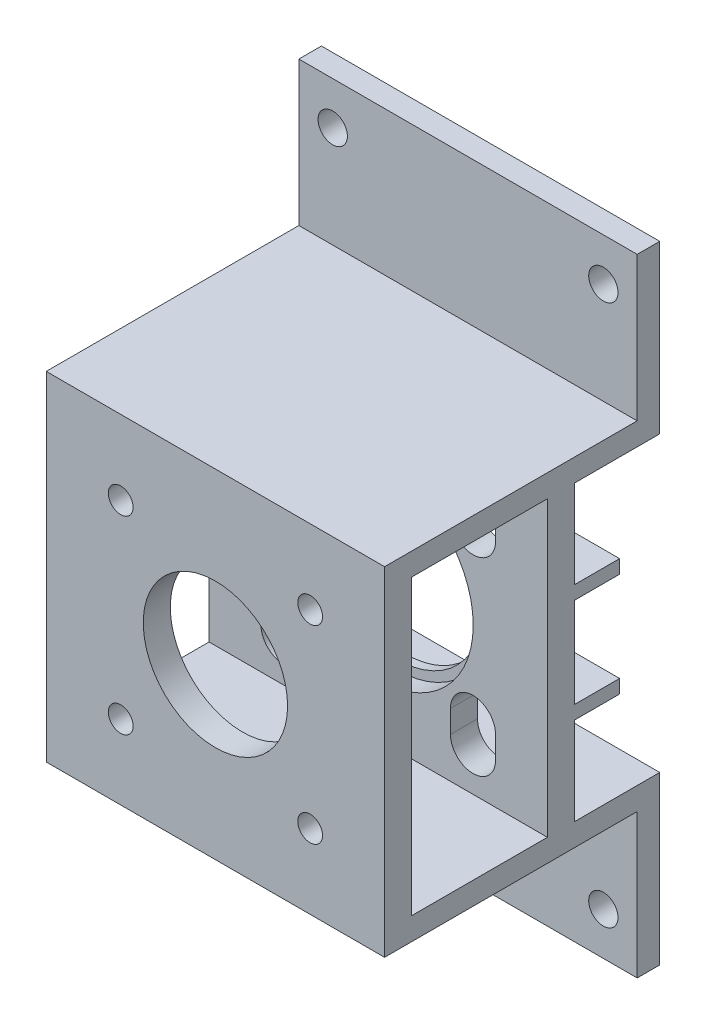
SolidWorks part; units mm, degrees
ref_plane "Front Plane" through (0, 0, 0) normal (0, 0, 1) x (1, 0, 0)
ref_plane "Top Plane" through (0, 0, 0) normal (0, 1, 0) x (1, 0, 0)
ref_plane "Right Plane" through (0, 0, 0) normal (1, 0, 0) x (0, 0, -1)
sketch "Sketch1" plane through (0, 0, 0) normal (0, 0, 1) x (1, 0, 0)
  line L1 (-37.5, -37.5) -> (37.5, -37.5)
  line L2 (-37.5, -37.5) -> (-37.5, 37.5)
  line L3 (-37.5, 37.5) -> (37.5, 37.5)
  line L4 (37.5, -37.5) -> (37.5, 37.5)
  line L5 (-37.5, -37.5) -> (37.5, 37.5) construction
  line L6 (-37.5, 37.5) -> (37.5, -37.5) construction
  line L7 (-21, -21) -> (21, -21) construction
  line L8 (-21, -21) -> (-21, 21) construction
  line L9 (-21, 21) -> (21, 21) construction
  line L10 (21, -21) -> (21, 21) construction
  line L11 (-21, -21) -> (21, 21) construction
  line L12 (-21, 21) -> (21, -21) construction
  circle A0 centre (21, 21) radius 2.75
  circle A1 centre (21, -21) radius 2.75
  circle A2 centre (-21, -21) radius 2.75
  circle A3 centre (-21, 21) radius 2.75
  circle A5 centre (0, 0) radius 16
  point P0 (0, 0)
  point P6 (0, 0)
  point P21 (0, 0)
  dimension "D3" = 5.5
  dimension "D5" = 32
  dimension "D1" = 75
  dimension "D2" = 42
  dimension "D4" = 4
extrude "Boss-Extrude1" add sketch "Sketch1" along normal blind 6
sketch "Sketch2" plane through (-37.5, 0, 0) normal (-1, 0, 0) x (0, 0, 1)
  line L0 (0, 37.5) -> (-50, 37.5)
  line L1 (-50, 37.5) -> (-50, 69.4641)
  line L2 (-50, 69.4641) -> (-55, 69.4641)
  line L3 (-55, 69.4641) -> (-55, 32.5)
  line L4 (-55, 32.5) -> (0, 32.5) construction
  line L5 (0, 37.5) -> (0, -37.5) construction
  line L6 (0, 32.5) -> (0, 37.5)
  line L7 (0, 0) -> (-49.6881, 0) construction
  line L8 (-55, -32.5) -> (0, -32.5) construction
  line L9 (0, -32.5) -> (0, -37.5)
  line L10 (-55, -69.4641) -> (-55, -32.5)
  line L11 (-50, -69.4641) -> (-55, -69.4641)
  line L12 (-50, -37.5) -> (-50, -69.4641)
  line L13 (0, -37.5) -> (-50, -37.5)
  line L14 (-30.0984, 32.5) -> (-30.0984, -32.5)
  line L15 (-36.0984, 32.5) -> (-36.0984, -32.5)
  line L16 (0, 32.5) -> (-30.0984, 32.5)
  line L17 (-55, 32.5) -> (-36.0984, 32.5)
  line L18 (0, -32.5) -> (-30.0984, -32.5)
  line L19 (-36.0984, -32.5) -> (-55, -32.5)
  dimension "D1" = 5
  dimension "D2" = 5
  dimension "D3" = 36.9641
  dimension "D4" = 50
  dimension "D5" = 6
extrude "Boss-Extrude2" add sketch "Sketch2" against normal up to surface (75 mm away) up to face at (37.5, 0, 3)
sketch "Sketch3" plane through (0, 0, -36.0984) normal (0, 0, -1) x (-1, 0, 0)
  circle A0 centre (0, 0) radius 21.05
  dimension "D1" = 42.1
extrude "Cut-Extrude1" cut sketch "Sketch3" against normal up to surface (6 mm away) up to face at (0, 0, -30.0984)
sketch "Sketch4" plane through (0, 0, -36.0984) normal (0, 0, -1) x (-1, 0, 0)
  circle A0 centre (0, 0) radius 21.05 construction
  circle A1 centre (0, 0) radius 21.05
  circle A2 centre (0, 0) radius 19.05
  dimension "D1" = 2
extrude "Boss-Extrude3" add sketch "Sketch4" against normal blind 2
sketch "Sketch5" plane through (0, 0, -50) normal (0, 0, 1) x (1, 0, 0)
  line L0 (37.5, -60) -> (-37.5, -60) construction
  line L1 (37.5, -37.5) -> (37.5, -69.4641) construction
  line L2 (-37.5, -69.4641) -> (-37.5, -37.5) construction
  line L3 (0, 0) -> (0, -60) construction
  circle A0 centre (30, -60) radius 3.25
  circle A1 centre (-30, -60) radius 3.25
  dimension "D2" = 6.5
  dimension "D3" = 6.5
  dimension "D4" = 30
  dimension "D5" = 30
  dimension "D1" = 60
extrude "Cut-Extrude2" cut sketch "Sketch5" against normal through all
mirror "Mirror1" about plane through (0, 0, 0) normal (0, 1, 0) of "Cut-Extrude2"
sketch "Sketch6" plane through (0, 0, -36.0984) normal (0, 0, -1) x (-1, 0, 0)
  line L0 (0, 32.5) -> (0, -32.5) construction
  line L1 (-37.5, 32.5) -> (37.5, 32.5) construction
  line L2 (-37.5, -32.5) -> (37.5, -32.5) construction
  line L3 (0, 0) -> (21, 0) construction
  line L4 (21, -21) -> (21, 21) construction
  line L7 (21, 23.5) -> (21, 18.5) construction
  line L10 (26, 23.5) -> (26, 18.5)
  line L11 (16, 23.5) -> (16, 18.5)
  line L12 (21, -23.5) -> (21, -18.5) construction
  line L13 (16, -23.5) -> (16, -18.5)
  line L14 (26, -23.5) -> (26, -18.5)
  line L15 (-21, -21) -> (-21, 21) construction
  line L16 (-21, -23.5) -> (-21, -18.5) construction
  line L17 (-16, -23.5) -> (-16, -18.5)
  line L18 (-26, -23.5) -> (-26, -18.5)
  line L19 (-21, 23.5) -> (-21, 18.5) construction
  line L20 (-26, 23.5) -> (-26, 18.5)
  line L21 (-16, 23.5) -> (-16, 18.5)
  arc A4 (26, 23.5) -> (16, 23.5) centre (21, 23.5) ccw
  arc A5 (16, 18.5) -> (26, 18.5) centre (21, 18.5) ccw
  arc A6 (16, -23.5) -> (26, -23.5) centre (21, -23.5) ccw
  arc A7 (26, -18.5) -> (16, -18.5) centre (21, -18.5) ccw
  arc A8 (-16, -23.5) -> (-26, -23.5) centre (-21, -23.5) cw
  arc A9 (-26, -18.5) -> (-16, -18.5) centre (-21, -18.5) cw
  arc A10 (-26, 23.5) -> (-16, 23.5) centre (-21, 23.5) cw
  arc A11 (-16, 18.5) -> (-26, 18.5) centre (-21, 18.5) cw
  point P12 (21, 0)
  point P14 (21, 21)
  point P20 (21, -21)
  point P31 (-21, -21)
  point P38 (-21, 21)
  point P43 (-21, 0)
  dimension "D1" = 21
  dimension "D2" = 5
  dimension "D3" = 10
  dimension "D4" = 42
extrude "Cut-Extrude3" cut sketch "Sketch6" against normal up to surface (6 mm away) up to face at (0, -21.05, -30.0984)
sketch "Sketch7" plane through (0, 0, -36.0984) normal (0, 0, -1) x (-1, 0, 0)
  line L0 (-37.5, -32.5) -> (-37.5, 32.5) construction
  line L2 (-23.5, -5) -> (-23.5, 5) construction
  line L5 (-37.5, 0) -> (0, 0) construction
  line L6 (-26, -3) -> (-21, -3)
  line L8 (-37.5, -13) -> (-37.5, -10)
  line L11 (-26, -3) -> (-26, -10)
  line L12 (-26, -10) -> (-37.5, -10)
  line L13 (-21, -3) -> (-21, -13)
  line L14 (-21, -13) -> (-37.5, -13)
  line L22 (-21, 13) -> (-37.5, 13)
  line L23 (-21, 3) -> (-21, 13)
  line L24 (-26, 10) -> (-37.5, 10)
  line L25 (-26, 3) -> (-26, 10)
  line L26 (-37.5, 13) -> (-37.5, 10)
  line L27 (-26, 3) -> (-21, 3)
  circle A1 centre (-23.5, -5) radius 1.25
  circle A3 centre (-23.5, 5) radius 1.25
  point P11 (-23.5, 0)
  point P29 (-13.5, 0)
  point P30 (-16.5, 0)
  dimension "D3" = 14
  dimension "D2" = 10
  dimension "D4" = 5
  dimension "D10" = 2.5
  dimension "D5" = 3
  dimension "D8" = 3
  dimension "D9" = 5
  dimension "D12" = 11.5
extrude "Boss-Extrude4" add sketch "Sketch7" along normal blind 10
sketch "Sketch11" plane through (21, 0, 0) normal (-1, 0, 0) x (0, 0, 1)
  line L0 (-36.0984, -3) -> (-36.0984, -13) construction
  line L1 (-36.0984, -13) -> (-42.5984, -13)
  line L2 (-36.0984, -13) -> (-36.0984, 13)
  line L3 (-36.0984, 13) -> (-42.5984, 13)
  line L4 (-42.5984, -13) -> (-42.5984, 13)
  line L5 (-46.0984, 13) -> (-36.0984, 13) construction
  line L6 (-46.0984, 3) -> (-46.0984, 13) construction
  dimension "D1" = 3.5
extrude "Cut-Extrude7" cut sketch "Sketch11" against normal blind 10
